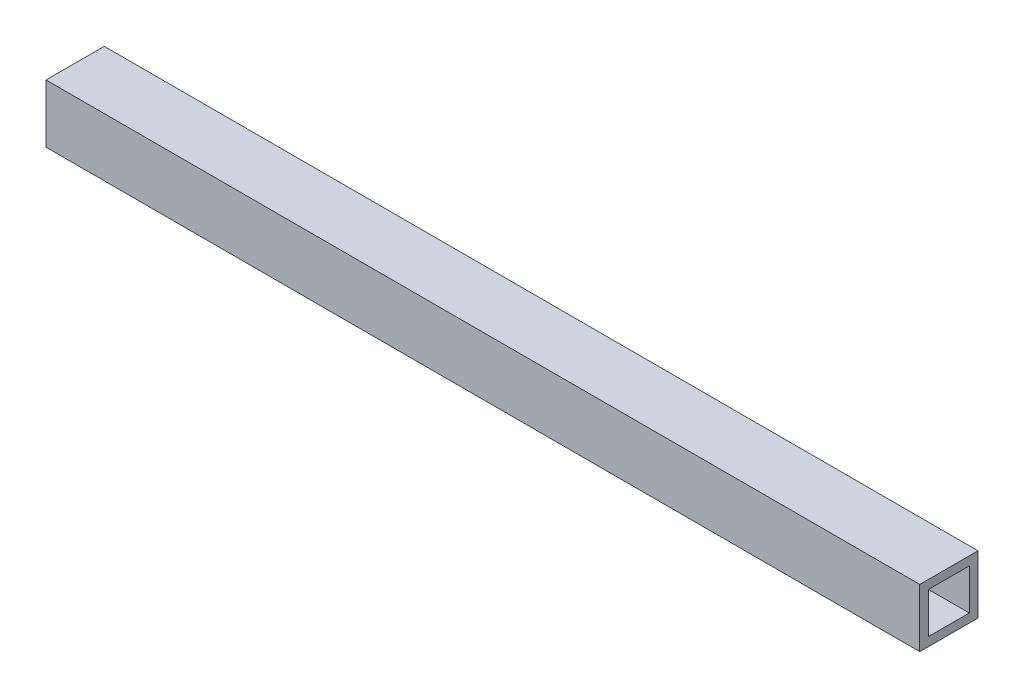
SolidWorks part; units mm, degrees
ref_plane "Alzado" through (0, 0, 0) normal (0, 0, 1) x (1, 0, 0)
ref_plane "Planta" through (0, 0, 0) normal (0, 1, 0) x (1, 0, 0)
ref_plane "Vista lateral" through (0, 0, 0) normal (1, 0, 0) x (0, 0, -1)
ref_plane "Plano1" through (0, -5, 0) normal (0, -1, 0) x (1, 0, 0)
sketch "Croquis1" plane through (0, -5, 0) normal (0, -1, 0) x (1, 0, 0)
  line L0 (0, 5) -> (0, -5)
  line L1 (0, -5) -> (150, -5)
  line L2 (150, -5) -> (150, 5)
  line L3 (150, 5) -> (0, 5)
  dimension "D1" = 150
extrude "Saliente-Extruir1" add sketch "Croquis1" against normal blind 10
sketch "Croquis2" plane through (0, 0, 0) normal (-1, 0, 0) x (0, 0, 1)
  line L0 (3.5, 3.5) -> (-3.5, 3.5)
  line L1 (-3.5, 3.5) -> (-3.5, -3.5)
  line L2 (-3.5, -3.5) -> (3.5, -3.5)
  line L3 (3.5, -3.5) -> (3.5, 3.5)
extrude "Cortar-Extruir1" cut sketch "Croquis2" against normal through all
sketch "Croquis3" plane through (0, 0, 5) normal (0, 0, 1) x (1, 0, 0)
  line L0 (25.01, -1.1667) -> (25.01, 3.5)
  line L1 (25.01, 3.5) -> (24.99, 3.5)
  line L2 (24.99, 3.5) -> (24.99, -1.1667)
  line L3 (24.99, -1.1667) -> (25.01, -1.1667)
extrude "Cortar-Extruir2" cut sketch "Croquis3" against normal blind 0.02
sketch "Croquis4" plane through (0, 0, 5) normal (0, 0, 1) x (1, 0, 0)
  line L0 (35.01, -1.1667) -> (35.01, 3.5)
  line L1 (35.01, 3.5) -> (34.99, 3.5)
  line L2 (34.99, 3.5) -> (34.99, -1.1667)
  line L3 (34.99, -1.1667) -> (35.01, -1.1667)
extrude "Cortar-Extruir3" cut sketch "Croquis4" against normal blind 0.02
sketch "Croquis5" plane through (0, 0, 5) normal (0, 0, 1) x (1, 0, 0)
  line L0 (45.01, -1.1667) -> (45.01, 3.5)
  line L1 (45.01, 3.5) -> (44.99, 3.5)
  line L2 (44.99, 3.5) -> (44.99, -1.1667)
  line L3 (44.99, -1.1667) -> (45.01, -1.1667)
extrude "Cortar-Extruir4" cut sketch "Croquis5" against normal blind 0.02
sketch "Croquis6" plane through (0, 0, 5) normal (0, 0, 1) x (1, 0, 0)
  line L0 (55.01, -1.1667) -> (55.01, 3.5)
  line L1 (55.01, 3.5) -> (54.99, 3.5)
  line L2 (54.99, 3.5) -> (54.99, -1.1667)
  line L3 (54.99, -1.1667) -> (55.01, -1.1667)
extrude "Cortar-Extruir5" cut sketch "Croquis6" against normal blind 0.02
sketch "Croquis7" plane through (0, 0, 5) normal (0, 0, 1) x (1, 0, 0)
  line L0 (65.01, -1.1667) -> (65.01, 3.5)
  line L1 (65.01, 3.5) -> (64.99, 3.5)
  line L2 (64.99, 3.5) -> (64.99, -1.1667)
  line L3 (64.99, -1.1667) -> (65.01, -1.1667)
extrude "Cortar-Extruir6" cut sketch "Croquis7" against normal blind 0.02
sketch "Croquis8" plane through (0, 0, 5) normal (0, 0, 1) x (1, 0, 0)
  line L0 (75.01, -1.1667) -> (75.01, 3.5)
  line L1 (75.01, 3.5) -> (74.99, 3.5)
  line L2 (74.99, 3.5) -> (74.99, -1.1667)
  line L3 (74.99, -1.1667) -> (75.01, -1.1667)
extrude "Cortar-Extruir7" cut sketch "Croquis8" against normal blind 0.02
sketch "Croquis9" plane through (0, 0, 5) normal (0, 0, 1) x (1, 0, 0)
  line L0 (85.01, -1.1667) -> (85.01, 3.5)
  line L1 (85.01, 3.5) -> (84.99, 3.5)
  line L2 (84.99, 3.5) -> (84.99, -1.1667)
  line L3 (84.99, -1.1667) -> (85.01, -1.1667)
extrude "Cortar-Extruir8" cut sketch "Croquis9" against normal blind 0.02
sketch "Croquis10" plane through (0, 0, 5) normal (0, 0, 1) x (1, 0, 0)
  line L0 (15.01, -1.1667) -> (15.01, 3.5)
  line L1 (15.01, 3.5) -> (14.99, 3.5)
  line L2 (14.99, 3.5) -> (14.99, -1.1667)
  line L3 (14.99, -1.1667) -> (15.01, -1.1667)
extrude "Cortar-Extruir9" cut sketch "Croquis10" against normal blind 0.02
